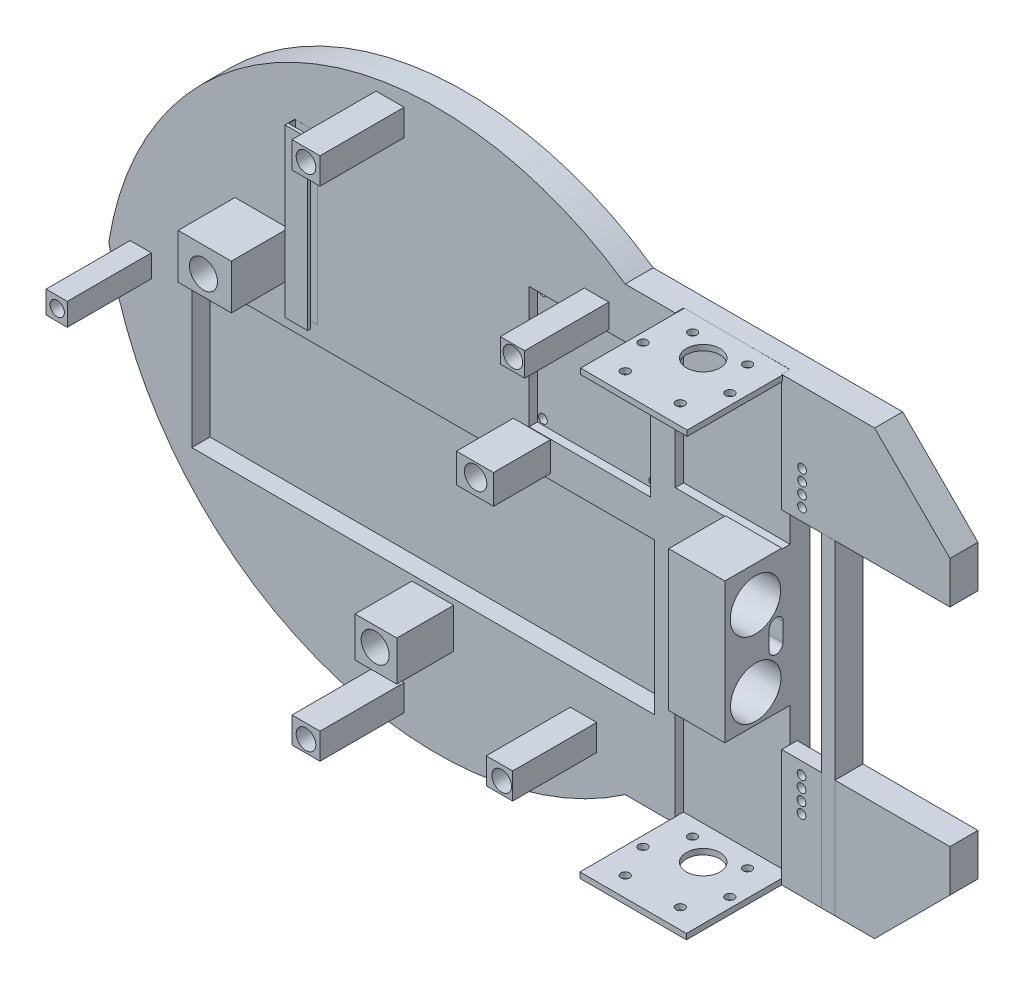
SolidWorks part; units mm, degrees
ref_plane "Front Plane" through (0, 0, 0) normal (0, 0, 1) x (1, 0, 0)
ref_plane "Top Plane" through (0, 0, 0) normal (0, 1, 0) x (1, 0, 0)
ref_plane "Right Plane" through (0, 0, 0) normal (1, 0, 0) x (0, 0, -1)
sketch "Sketch1" plane through (0, 0, 0) normal (0, 0, 1) x (1, 0, 0)
  line L1 (0, 0) -> (0, -37)
  line L2 (0, 37) -> (60, 37)
  line L3 (0, -37) -> (60, -37)
  line L4 (60, 37) -> (60, 52)
  line L5 (60, -37) -> (60, -52)
  line L6 (60, 52) -> (33.1299, 78.8701)
  line L7 (33.1299, 78.8701) -> (-55.8501, 78.8701)
  line L8 (60, -52) -> (33.1299, -78.8701)
  line L9 (33.1299, -78.8701) -> (-55.8501, -78.8701)
  line L10 (-55.8501, 78.8701) -> (-55.8501, 156.9436) construction
  line L11 (-55.8501, 156.9436) -> (-55.8501, -275.005) construction
  line L22 (0, 37) -> (0, 0)
  line L24 (-123.0632, 99.8019) -> (-270.1361, 99.8019) construction
  line L25 (-123.0632, 18.6512) -> (-123.0632, 134.1641) construction
  line L26 (-123.0632, -18.5763) -> (-123.0632, -116.9478) construction
  line L27 (-123.0632, -99.7887) -> (-269.8976, -99.7887) construction
  arc A7 (-239.9999, -0.1587) -> (-55.8501, 78.8701) centre (-123.0632, -18.5763) cw
  arc A8 (-55.8501, -78.8701) -> (-239.9999, -0.1587) centre (-123.0632, 18.6512) cw
  dimension "D11" = 199.5908
  dimension "D12" = 240
  dimension "D10" = 157.7401
  dimension "D1" = 37
  dimension "D2" = 37
  dimension "D3" = 60
  dimension "D4" = 15
  dimension "D5" = 15
  dimension "D6" = 135
  dimension "D7" = 38
  dimension "D8" = 38
  dimension "D9" = 135
  dimension "D15" = 88.98
  dimension "D16" = 88.98
extrude "Boss-Extrude1" add sketch "Sketch1" along normal blind 10 and the other way blind 0.01
sketch "Sketch3" plane through (0, 0, 10) normal (0, 0, 1) x (1, 0, 0)
  line L0 (33.1299, 78.8701) -> (-55.8501, 78.8701) construction
  line L1 (-38, 78.8701) -> (0, 78.8701)
  line L2 (-38, 78.8701) -> (-38, 24.8701)
  line L3 (-38, 24.8701) -> (0, 24.8701)
  line L4 (0, 78.8701) -> (0, 24.8701)
  dimension "D1" = 54
extrude "Cut-Extrude1" cut sketch "Sketch3" against normal blind 3 contours L2 L1 L4 L3
sketch "Sketch5" plane through (0, 0, 10) normal (0, 0, 1) x (1, 0, 0)
  line L0 (-55.8501, -78.8701) -> (33.1299, -78.8701) construction
  line L1 (-38, -24.8701) -> (0, -24.8701)
  line L2 (-38, -24.8701) -> (-38, -78.8701)
  line L3 (-38, -78.8701) -> (0, -78.8701)
  line L4 (0, -24.8701) -> (0, -78.8701)
  dimension "D1" = 54
extrude "Cut-Extrude3" cut sketch "Sketch5" against normal blind 3
sketch "Sketch7" plane through (0, 0, 10) normal (0, 0, 1) x (1, 0, 0)
  line L1 (-210.4131, 5.0562) -> (-45.4131, 5.0562)
  line L2 (-210.4131, 5.0562) -> (-210.4131, -48.9438)
  line L3 (-210.4131, -48.9438) -> (-45.4131, -48.9438)
  line L4 (-45.4131, 5.0562) -> (-45.4131, -48.9438)
  dimension "D1" = 54
  dimension "D2" = 165
extrude "Cut-Extrude4" cut sketch "Sketch7" against normal blind 6.5
sketch "Sketch8" plane through (0, 0, 10) normal (0, 0, 1) x (1, 0, 0)
  line L1 (-162.9927, 67.8133) -> (-84.7927, 67.8133)
  line L2 (-162.9927, 67.8133) -> (-162.9927, 10.3133)
  line L3 (-162.9927, 10.3133) -> (-84.7927, 10.3133)
  line L4 (-84.7927, 67.8133) -> (-84.7927, 10.3133)
  dimension "D1" = 78.2
  dimension "D2" = 57.5
extrude "Cut-Extrude5" [suppressed] cut sketch "Sketch8" against normal blind 3
sketch "Sketch9" plane through (0, 0, 10) normal (0, 0, 1) x (1, 0, 0)
  line L1 (-195, 36) -> (-176, 36)
  line L2 (-195, 36) -> (-195, 20)
  line L3 (-195, 20) -> (-176, 20)
  line L4 (-176, 36) -> (-176, 20)
  line L5 (-95.7317, 17.4542) -> (-82.493, 17.4542)
  line L6 (-95.7317, 17.4542) -> (-95.7317, 7.0108)
  line L7 (-95.7317, 7.0108) -> (-82.493, 7.0108)
  line L8 (-82.493, 17.4542) -> (-82.493, 7.0108)
  line L9 (-131.8867, -50.9252) -> (-116.9909, -50.9252)
  line L10 (-131.8867, -50.9252) -> (-131.8867, -65.1638)
  line L11 (-131.8867, -65.1638) -> (-116.9909, -65.1638)
  line L12 (-116.9909, -50.9252) -> (-116.9909, -65.1638)
extrude "Boss-Extrude2" add sketch "Sketch9" along normal blind 20.3
sketch "Sketch15" plane through (0, 0, 10) normal (0, 0, 1) x (1, 0, 0)
  line L0 (0, -24.8701) -> (0, 24.8701) construction
  line L1 (-20, 25.2016) -> (0, 25.2016)
  line L2 (-20, 25.2016) -> (-20, -24.7984)
  line L3 (-20, -24.7984) -> (0, -24.7984)
  line L4 (0, 25.2016) -> (0, -24.7984)
  dimension "D1" = 50
  dimension "D2" = 20
extrude "Boss-Extrude3" add sketch "Sketch15" along normal blind 20.3
sketch "Sketch16" plane through (0, 0, 10) normal (0, 0, 1) x (1, 0, 0)
  line L1 (-232.4208, 4) -> (-224.8235, 4)
  line L2 (-232.4208, 4) -> (-232.4208, -4)
  line L3 (-232.4208, -4) -> (-224.8235, -4)
  line L4 (-224.8235, 4) -> (-224.8235, -4)
  line L9 (-134.6881, 94.0493) -> (-144.6881, 94.0493)
  line L10 (-134.6881, 94.0493) -> (-134.6881, 84.6493)
  line L11 (-134.6881, 84.6493) -> (-144.6881, 84.6493)
  line L12 (-144.6881, 94.0493) -> (-144.6881, 84.6493)
  line L13 (-61.6779, 70.3488) -> (-70.3779, 70.3488)
  line L14 (-61.6779, 70.3488) -> (-61.6779, 61.8488)
  line L15 (-61.6779, 61.8488) -> (-70.3779, 61.8488)
  line L16 (-70.3779, 70.3488) -> (-70.3779, 61.8488)
  line L17 (-65.9779, -61.6233) -> (-75.3779, -61.6233)
  line L18 (-65.9779, -61.6233) -> (-65.9779, -70.9233)
  line L19 (-65.9779, -70.9233) -> (-75.3779, -70.9233)
  line L20 (-75.3779, -61.6233) -> (-75.3779, -70.9233)
  line L21 (-134.6881, -83.6815) -> (-144.6881, -83.6815)
  line L22 (-134.6881, -83.6815) -> (-134.6881, -92.9815)
  line L23 (-134.6881, -92.9815) -> (-144.6881, -92.9815)
  line L24 (-144.6881, -83.6815) -> (-144.6881, -92.9815)
  point P4 (0, 0)
  point P5 (0, 0)
  point P6 (0, 0)
  point P7 (0, 0)
extrude "Boss-Extrude4" add sketch "Sketch16" along normal blind 30
sketch "Sketch17" plane through (0, 0, 0) normal (0, 0, 1) x (1, 0, 0)
  circle A1 centre (-228.4208, 0) radius 2.55
  circle A2 centre (-139.6881, 89.6493) radius 3.5
  circle A3 centre (-65.8779, 66.3488) radius 3.5
  circle A4 centre (-69.8779, -66.6233) radius 3.5
  circle A5 centre (-139.6881, -88.6815) radius 3.5
  point P0 (0, 0)
extrude "Cut-Extrude17" cut sketch "Sketch17" along normal through all
sketch "Sketch18" plane through (0, 0, 10) normal (0, 0, 1) x (1, 0, 0)
  line L1 (-90.1245, 61) -> (-46.7245, 61)
  line L2 (-90.1245, 61) -> (-90.1245, 17.6)
  line L3 (-90.1245, 17.6) -> (-46.7245, 17.6)
  line L4 (-46.7245, 61) -> (-46.7245, 17.6)
  dimension "D1" = 43.4
  dimension "43.4" = 43.4
extrude "Cut-Extrude18" cut sketch "Sketch18" against normal blind 3
sketch "Sketch20" plane through (0, 0, 0) normal (0, 0, 1) x (1, 0, 0)
  circle A0 centre (-185.9471, 27.1121) radius 5
  circle A1 centre (-124.7094, -57.6129) radius 5
  circle A2 centre (-88.8879, 12.7504) radius 4
extrude "Cut-Extrude20" cut sketch "Sketch20" along normal through all
sketch "Sketch21" plane through (0, 0, 0) normal (1, 0, 0) x (0, 0, -1)
  line L0 (-3.8276, 29.0855) -> (-3.8276, -37.1575) construction
  line L1 (-6.4886, 28.3852) -> (-6.4886, -37.2976) construction
  line L2 (-5.0881, 28.1051) -> (-5.0881, -37.5777) construction
  line L3 (-11.99, 2.3019) -> (-12.0559, -4.1532) construction
  line L4 (-9.4916, 2.2764) -> (-9.5574, -4.1787)
  line L5 (-14.4885, 2.3274) -> (-14.5544, -4.1277)
  circle A0 centre (-19.3619, 12.3718) radius 9
  circle A1 centre (-19.2654, -14.6282) radius 9
  arc A2 (-9.4916, 2.2764) -> (-14.4885, 2.3274) centre (-11.99, 2.3019) ccw
  arc A3 (-14.5544, -4.1277) -> (-9.5574, -4.1787) centre (-12.0559, -4.1532) ccw
  point P12 (-12.023, -0.9256)
  dimension "D1" = 18
  dimension "D2" = 18
  dimension "D3" = 27
extrude "Cut-Extrude21" cut sketch "Sketch21" against normal up to surface (20 mm away) up to face at (-20, 5.1353, 18.12)
sketch "Sketch22" plane through (0, 0, 7) normal (0, 0, 1) x (1, 0, 0)
  circle A0 centre (-88.1686, 58.9795) radius 1.55
  circle A1 centre (-48.7686, 58.9795) radius 1.55
  circle A2 centre (-48.7686, 19.5795) radius 1.55
  circle A3 centre (-88.1686, 19.5795) radius 1.55
  dimension "D1" = 2
  dimension "D2" = 2
extrude "Cut-Extrude23" cut sketch "Sketch22" against normal through all
sketch "Sketch25" plane through (0, 0, 10) normal (0, 0, 1) x (1, 0, 0)
  line L1 (-173.6964, 70.8495) -> (-165.5964, 70.8495)
  line L2 (-173.6964, 70.8495) -> (-173.6964, 11.3495)
  line L3 (-173.6964, 11.3495) -> (-165.5964, 11.3495)
  line L4 (-165.5964, 70.8495) -> (-165.5964, 11.3495)
  dimension "D1" = 8.1
  dimension "D2" = 59.5
extrude "Boss-Extrude5" add sketch "Sketch25" along normal blind 3.5
sketch "Sketch26" plane through (0, 11.3495, 0) normal (0, -1, 0) x (1, 0, 0)
  line L0 (-172.679, 10.0037) -> (-152.674, 9.9893) construction
  line L1 (-152.674, 9.9893) -> (-152.6595, 14.6073) construction
  line L2 (-165.5928, 10.0085) -> (-173.4128, 10.0085)
  line L3 (-173.4128, 10.0085) -> (-173.4128, 12.4083)
  line L4 (-173.4128, 12.4083) -> (-165.5928, 12.4083)
  line L5 (-165.5928, 12.4083) -> (-165.5928, 10.0083)
  line M7 (-165.5964, 10) -> (-165.5964, 13.5)
extrude "Cut-Extrude24" cut sketch "Sketch26" against normal up to surface (59.5 mm away) contours L4 L3 L2 M7 up to face at (-169.6464, 70.8495, 11.75)
sketch "Sketch28" plane through (0, -78.8701, 0) normal (0, -1, 0) x (1, 0, 0)
  line L1 (14.2266, 10.0076) -> (18.9795, 10.0076)
  line L2 (14.2266, 10.0076) -> (14.2266, 0.0598)
  line L3 (14.2266, 0.0598) -> (18.9795, 0.0598)
  line L4 (18.9795, 10.0076) -> (18.9795, 0.0598)
extrude "Boss-Extrude6" add sketch "Sketch28" against normal up to surface (115.8701 mm away) up to face at (24, 37, 5.396)
sketch "Sketch30" plane through (0, 0, -0.01) normal (0, 0, -1) x (-1, 0, 0)
  line L0 (0.5881, -0.0011) -> (-26.6848, -0.0585) construction
  line L1 (0, -62) -> (-14.12, -62)
  line L2 (0, -62) -> (0, -37)
  line L3 (0, -37) -> (-14.12, -37)
  line L4 (-14.12, -62) -> (-14.12, -37)
  line L5 (-14.3807, 61.9354) -> (-14.2755, 36.9356)
  line L6 (-0.1557, 36.995) -> (-14.2755, 36.9356)
  line L7 (-0.2608, 61.9948) -> (-0.1557, 36.995)
  line L8 (-0.2608, 61.9948) -> (-14.3807, 61.9354)
  dimension "D1" = 25
  dimension "D2" = 14.12
extrude "Cut-Extrude25" cut sketch "Sketch30" against normal blind 4.5
sketch "Sketch33" plane through (0, 0, -0.01) normal (0, 0, -1) x (-1, 0, 0)
  line L0 (0, 0) -> (-115.8951, -0.2361) construction
  circle A0 centre (-7.06, -53.4) radius 1.55
  circle A1 centre (-7.06, -49.4) radius 1.55
  circle A2 centre (-7.06, -45.4) radius 1.55
  circle A3 centre (-7.06, -41.4) radius 1.55
  circle A4 centre (-7.2286, 41.3709) radius 1.55
  circle A5 centre (-7.2449, 45.3709) radius 1.55
  circle A6 centre (-7.2612, 49.3708) radius 1.55
  circle A7 centre (-7.2775, 53.3708) radius 1.55
  dimension "D1" = 4
extrude "Cut-Extrude26" cut sketch "Sketch33" against normal up to surface (10.01 mm away) up to face at (7.1133, -57.935, 10)
sketch "Sketch34" plane through (0, 0, 10) normal (0, 0, 1) x (1, 0, 0)
  line L0 (0, 0) -> (85.4359, -0.2266) construction
  line L1 (53.8089, -34.3247) -> (61.9289, -40.2214)
  line L2 (53.8089, -34.3247) -> (57.1772, -29.6864)
  line L3 (61.9289, -40.2214) -> (65.2973, -35.5831)
  line L4 (57.1772, -29.6864) -> (65.2973, -35.5831)
  line L5 (62.1414, 39.8924) -> (65.4851, 35.2362)
  line L6 (57.3338, 29.3826) -> (65.4851, 35.2362)
  line L7 (53.9902, 34.0388) -> (57.3338, 29.3826)
  line L8 (53.9902, 34.0388) -> (62.1414, 39.8924)
extrude "Cut-Extrude27" [suppressed] cut sketch "Sketch34" against normal through all
sketch "Sketch36" plane through (0, 0, 7) normal (0, 0, 1) x (1, 0, 0)
  line L0 (0, 0) -> (106.9048, -0.1896) construction
  line L1 (0.2795, 78.8146) -> (0.2724, 76.8146)
  line L2 (0, -78.8151) -> (-38, -78.8151)
  line L3 (0, -78.8151) -> (0, -76.8151)
  line L4 (0, -76.8151) -> (-38, -76.8151)
  line L5 (-38, -78.8151) -> (-38, -76.8151)
  line L6 (-37.7202, 78.9494) -> (-37.7273, 76.9494)
  line L7 (0.2724, 76.8146) -> (-37.7273, 76.9494)
  line L8 (0.2795, 78.8146) -> (-37.7202, 78.9494)
  dimension "D1" = 2
extrude "Boss-Extrude7" add sketch "Sketch36" along normal blind 37
sketch "Sketch39" plane through (0, -78.8151, 0) normal (0, -1, 0) x (1, 0, 0)
  line L1 (-46.4365, 25) -> (22.9075, 25) construction
  line L4 (31.9978, 332) -> (-461.8231, 332) construction
  circle A1 centre (-19, 19) radius 6
  circle A2 centre (-34.4996, 25.0106) radius 1.55
  circle A3 centre (-3.5639, 24.9888) radius 1.55
  circle A4 centre (-28.8192, 37.0106) radius 1.55
  circle A5 centre (-9.1774, 36.9888) radius 1.55
  circle A6 centre (-28.82, 13.0106) radius 1.55
  circle A7 centre (-9.2305, 12.9888) radius 1.55
  point P18 (6.9989, 178.85)
  dimension "D1" = 12
  dimension "D5" = 12
  dimension "D6" = 12
  dimension "D7" = 12
  dimension "D8" = 12
  dimension "D2" = 19
extrude "Cut-Extrude28" cut sketch "Sketch39" against normal up to surface (2 mm away) up to face at (-19, -76.8151, 20.3333)
sketch "Sketch42" plane through (0.2795, 78.8146, 0) normal (0.0035, 1, 0) x (1, -0.0035, 0)
  circle A7 centre (-19.2797, -19) radius 6
  circle A9 centre (-29.0701, -13) radius 1.55
  circle A10 centre (-3.7784, -25) radius 1.55
  circle A11 centre (-9.4641, -13) radius 1.55
  circle A12 centre (-34.7723, -25) radius 1.55
  circle A13 centre (-29.0965, -37) radius 1.55
  circle A14 centre (-9.4734, -37) radius 1.55
  dimension "D1" = 12
  dimension "D5" = 6
  dimension "D6" = 6
  dimension "D7" = 6
  dimension "D8" = 6
  dimension "D9" = 18
  dimension "D10" = 18
  dimension "D2" = 19
extrude "Cut-Extrude29" cut sketch "Sketch42" against normal up to surface (2 mm away) up to face at (-12.485, 76.8599, 20.3333)
